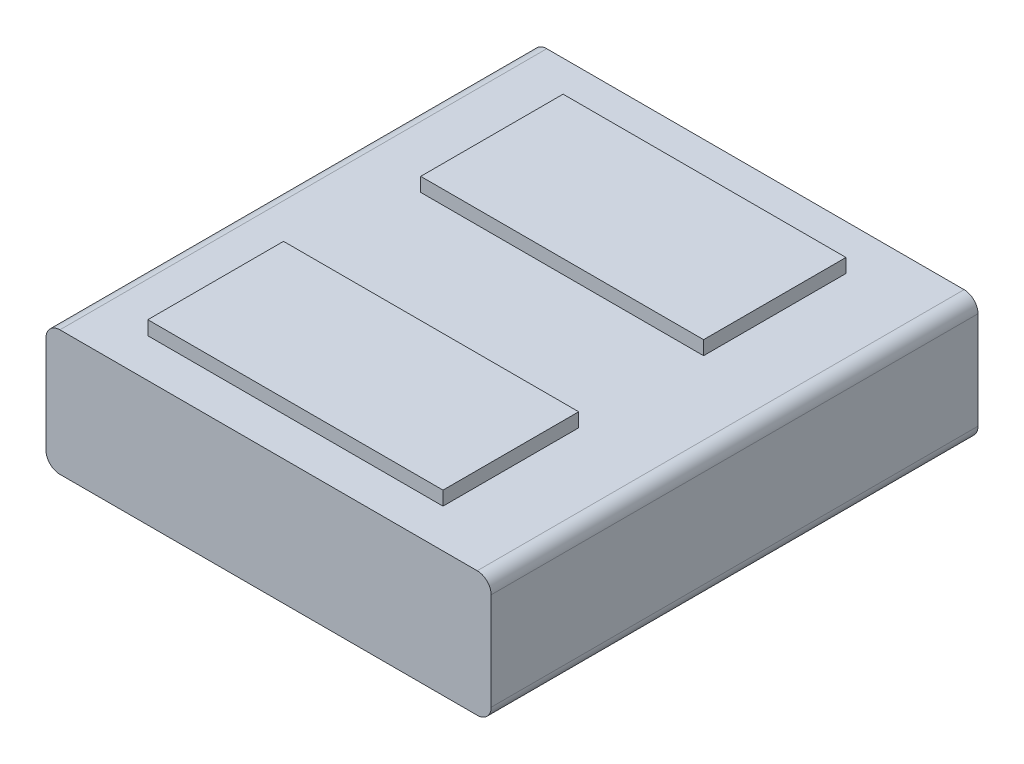
SolidWorks part; units mm, degrees
ref_plane "前基準面" through (0, 0, 0) normal (0, 0, 1) x (1, 0, 0)
ref_plane "上基準面" through (0, 0, 0) normal (0, 1, 0) x (1, 0, 0)
ref_plane "右基準面" through (0, 0, 0) normal (1, 0, 0) x (0, 0, -1)
sketch "草圖1" plane through (0, 0, 0) normal (0, 0, 1) x (1, 0, 0)
  line L1 (0, 0) -> (64, 0)
  line L2 (0, 0) -> (0, 18)
  line L3 (0, 18) -> (64, 18)
  line L4 (64, 0) -> (64, 18)
  dimension "D1" = 64
  dimension "D2" = 18
extrude "填料-伸長1" add sketch "草圖1" along normal blind 70
fillet "圓角1" radius 2 4 edges at (64, 0, 35) (0, 0, 35) (0, 18, 35) (64, 18, 35)
sketch "草圖2" plane through (0, 18, 0) normal (0, 1, 0) x (1, 0, 0)
  line L1 (9.0615, -64.4212) -> (51.4997, -64.4212)
  line L2 (9.0615, -64.4212) -> (9.0615, -44.9113)
  line L3 (9.0615, -44.9113) -> (51.4997, -44.9113)
  line L4 (51.4997, -64.4212) -> (51.4997, -44.9113)
  line L5 (10.8302, -26.9553) -> (51.4997, -26.9553)
  line L6 (10.8302, -26.9553) -> (10.8302, -6.4851)
  line L7 (10.8302, -6.4851) -> (51.4997, -6.4851)
  line L8 (51.4997, -26.9553) -> (51.4997, -6.4851)
extrude "填料-伸長2" add sketch "草圖2" along normal blind 2 separate body
